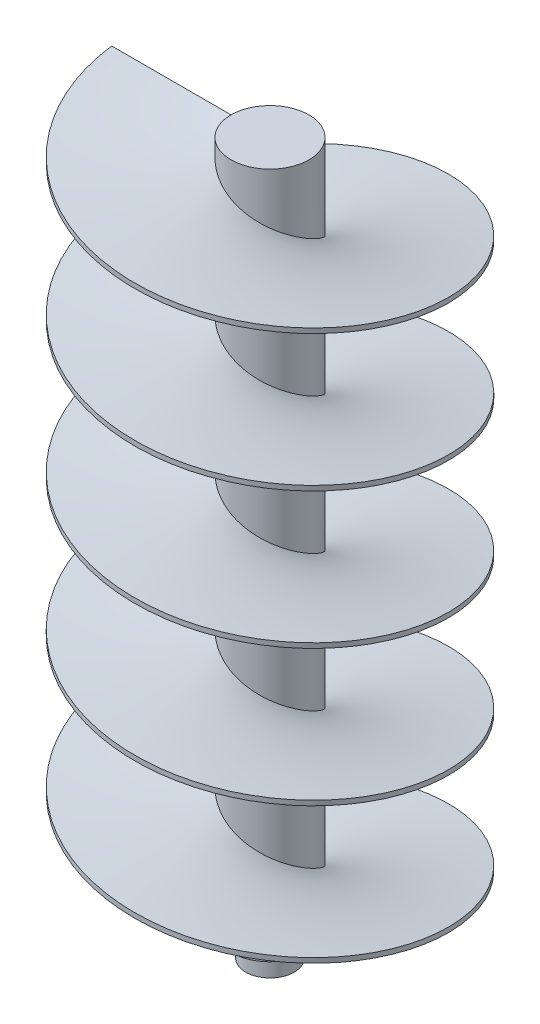
SolidWorks part; units mm, degrees
ref_plane "前基準面" through (0, 0, 0) normal (0, 0, 1) x (1, 0, 0)
ref_plane "上基準面" through (0, 0, 0) normal (0, 1, 0) x (1, 0, 0)
ref_plane "右基準面" through (0, 0, 0) normal (1, 0, 0) x (0, 0, -1)
sketch "草圖4" plane through (0, 0, 0) normal (0, 1, 0) x (1, 0, 0)
  circle A0 centre (0, 0) radius 32.5
  dimension "D1" = 65
curve "螺旋曲線/渦捲線1" pitch 28 height 140 turns 5
ref_plane "平面1" through (0, 0, 0) normal (0, 0, 1) x (1, 0, 0)
sketch "草圖5" plane through (0, 0, 0) normal (0, 0, 1) x (1, 0, 0)
  line L1 (-32.5, 139.9986) -> (-7.5, 139.9986)
  line L2 (-32.5, 139.9986) -> (-32.5, 138.9986)
  line L3 (-32.5, 138.9986) -> (-7.5, 138.9986)
  line L4 (-7.5, 139.9986) -> (-7.5, 138.9986)
  spline S0 degree 3 poles (-32.5, 0) (-32.5, 0.3694) (-31.823, 1.1115) (-28.8395, 2.2221) (-24.0723, 3.3334) (-17.8164, 4.4444) (-10.4586, 5.5556) (-2.454, 6.6667) (5.7023, 7.7778) (13.506, 8.8889) (20.4745, 10) (26.1766, 11.1111) (30.2599, 12.2222) (32.4717, 13.3333) (32.6753, 14.4444) (30.8581, 15.5556) (27.1324, 16.6667) (21.7288, 17.7778) (14.9813, 18.8889) (7.3073, 20) (-0.8187, 21.1111) (-8.894, 22.2222) (-16.4192, 23.3333) (-22.929, 24.4444) (-28.0208, 25.5556) (-31.3796, 26.6667) (-32.7977, 27.7778) (-32.1874, 28.8889) (-29.5865, 30) (-25.1557, 31.1111) (-19.1693, 32.2222) (-11.9972, 33.3333) (-4.0833, 34.4444) (4.0833, 35.5556) (11.9972, 36.6667) (19.1693, 37.7778) (25.1557, 38.8889) (29.5865, 40) (32.1874, 41.1111) (32.7977, 42.2222) (31.3796, 43.3333) (28.0208, 44.4444) (22.929, 45.5556) (16.4192, 46.6667) (8.894, 47.7778) (0.8187, 48.8889) (-7.3073, 50) (-14.9813, 51.1111) (-21.7288, 52.2222) (-27.1324, 53.3333) (-30.8581, 54.4444) (-32.6753, 55.5556) (-32.4717, 56.6667) (-30.2599, 57.7778) (-26.1766, 58.8889) (-20.4745, 60) (-13.506, 61.1111) (-5.7023, 62.2222) (2.454, 63.3333) (10.4586, 64.4444) (17.8164, 65.5556) (24.0723, 66.6667) (28.8395, 67.7778) (31.823, 68.8889) (32.8385, 70) (31.823, 71.1111) (28.8395, 72.2222) (24.0723, 73.3333) (17.8164, 74.4444) (10.4586, 75.5556) (2.454, 76.6667) (-5.7023, 77.7778) (-13.506, 78.8889) (-20.4745, 80) (-26.1766, 81.1111) (-30.2599, 82.2222) (-32.4717, 83.3333) (-32.6753, 84.4444) (-30.8581, 85.5556) (-27.1324, 86.6667) (-21.7288, 87.7778) (-14.9813, 88.8889) (-7.3073, 90) (0.8187, 91.1111) (8.894, 92.2222) (16.4192, 93.3333) (22.929, 94.4444) (28.0208, 95.5556) (31.3796, 96.6667) (32.7977, 97.7778) (32.1874, 98.8889) (29.5865, 100) (25.1557, 101.1111) (19.1693, 102.2222) (11.9972, 103.3333) (4.0833, 104.4444) (-4.0833, 105.5556) (-11.9972, 106.6667) (-19.1693, 107.7778) (-25.1557, 108.8889) (-29.5865, 110) (-32.1874, 111.1111) (-32.7977, 112.2222) (-31.3796, 113.3333) (-28.0208, 114.4444) (-22.929, 115.5556) (-16.4192, 116.6667) (-8.894, 117.7778) (-0.8187, 118.8889) (7.3073, 120) (14.9813, 121.1111) (21.7288, 122.2222) (27.1324, 123.3333) (30.8581, 124.4444) (32.6753, 125.5556) (32.4717, 126.6667) (30.2599, 127.7778) (26.1766, 128.8889) (20.4745, 130) (13.506, 131.1111) (5.7023, 132.2222) (-2.454, 133.3333) (-10.4586, 134.4444) (-17.8164, 135.5556) (-24.0723, 136.6666) (-28.8395, 137.7779) (-31.823, 138.8885) (-32.5, 139.6306) (-32.5, 140) knots 0 0 0 0 0.007937 0.015873 0.02381 0.031746 0.039683 0.047619 0.055556 0.063492 0.071429 0.079365 0.087302 0.095238 0.103175 0.111111 0.119048 0.126984 0.134921 0.142857 0.150794 0.15873 0.166667 0.174603 0.18254 0.190476 0.198413 0.206349 0.214286 0.222222 0.230159 0.238095 0.246032 0.253968 0.261905 0.269841 0.277778 0.285714 0.293651 0.301587 0.309524 0.31746 0.325397 0.333333 0.34127 0.349206 0.357143 0.365079 0.373016 0.380952 0.388889 0.396825 0.404762 0.412698 0.420635 0.428571 0.436508 0.444444 0.452381 0.460317 0.468254 0.47619 0.484127 0.492063 0.5 0.507937 0.515873 0.52381 0.531746 0.539683 0.547619 0.555556 0.563492 0.571429 0.579365 0.587302 0.595238 0.603175 0.611111 0.619048 0.626984 0.634921 0.642857 0.650794 0.65873 0.666667 0.674603 0.68254 0.690476 0.698413 0.706349 0.714286 0.722222 0.730159 0.738095 0.746032 0.753968 0.761905 0.769841 0.777778 0.785714 0.793651 0.801587 0.809524 0.81746 0.825397 0.833333 0.84127 0.849206 0.857143 0.865079 0.873016 0.880952 0.888889 0.896825 0.904762 0.912698 0.920635 0.928571 0.936508 0.944444 0.952381 0.960317 0.968254 0.97619 0.984127 0.992063 1 1 1 1 construction
  point P0 (-32.5, 139.9986)
  dimension "D1" = 25
  dimension "D2" = 1
sweep "掃出1" add profiles "草圖5" path "螺旋曲線/渦捲線1"
sketch "草圖6" plane through (0, 0, 0) normal (0, 1, 0) x (1, 0, 0)
  circle A0 centre (0, 0) radius 8
  dimension "D1" = 16
extrude "填料-伸長1" add sketch "草圖6" along normal blind 140
sketch "草圖7" plane through (0, 0, 0) normal (0, -1, 0) x (1, 0, 0)
  circle A0 centre (0, 0) radius 8
extrude "填料-伸長2" add sketch "草圖7" along normal blind 1
sketch "草圖8" plane through (0, -1, 0) normal (0, -1, 0) x (1, 0, 0)
  circle A0 centre (0, 0) radius 5
  dimension "D1" = 10
extrude "填料-伸長3" add sketch "草圖8" along normal blind 5
